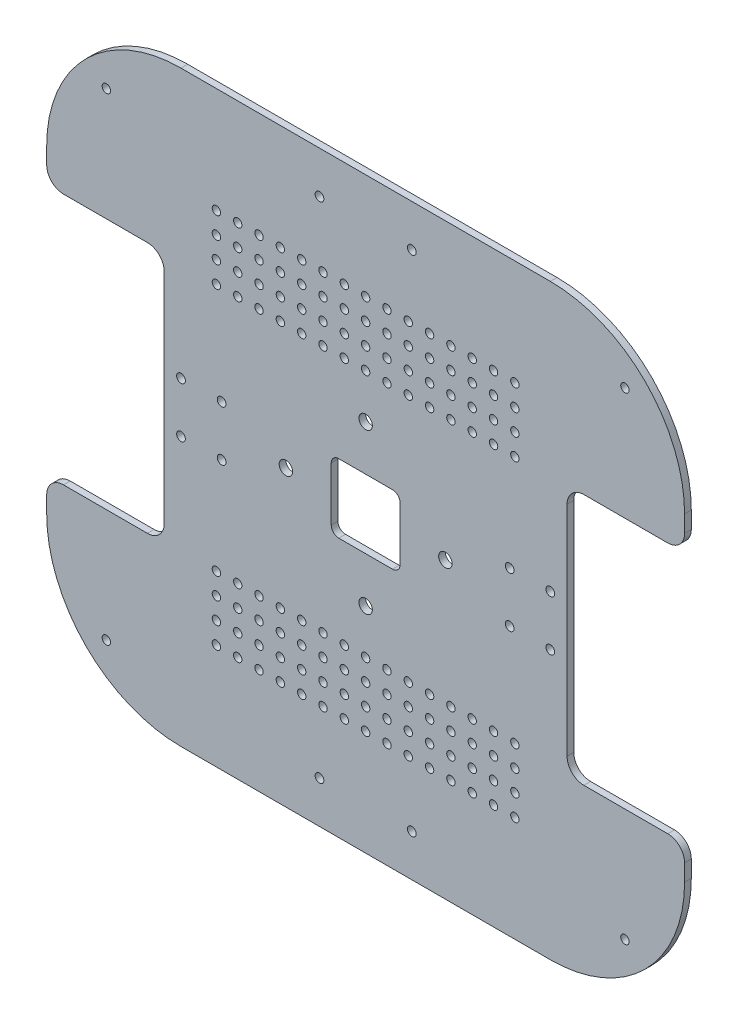
SolidWorks part; units mm, degrees
ref_plane "前视基准面" through (0, 0, 0) normal (0, 0, 1) x (1, 0, 0)
ref_plane "上视基准面" through (0, 0, 0) normal (0, 1, 0) x (1, 0, 0)
ref_plane "右视基准面" through (0, 0, 0) normal (1, 0, 0) x (0, 0, -1)
sketch "草图1" plane through (0, 0, 0) normal (0, 0, 1) x (1, 0, 0)
  line L0 (0, 0) -> (0, 255.003) construction
  line L1 (-190, 175) -> (190, 175)
  line L2 (-190, 175) -> (-190, 75)
  line L3 (-190, -175) -> (190, -175)
  line L4 (190, 175) -> (190, 75)
  line L5 (-190, 175) -> (190, -175) construction
  line L6 (-190, -175) -> (190, 175) construction
  line L7 (-190, -75) -> (-120, -75)
  line L9 (-190, 75) -> (-120, 75)
  line L10 (-120, -75) -> (-120, 75)
  line L11 (0, -175) -> (0, 175) construction
  line L12 (-20.5, -20.5) -> (20.5, -20.5)
  line L13 (190, 75) -> (120, 75)
  line L14 (120, -75) -> (120, 75)
  line L15 (190, -75) -> (120, -75)
  line L17 (190, -75) -> (190, -175)
  line L18 (-190, -75) -> (-190, -175)
  line L19 (-20.5, -20.5) -> (-20.5, 20.5)
  line L20 (-20.5, 20.5) -> (20.5, 20.5)
  line L21 (20.5, -20.5) -> (20.5, 20.5)
  line L22 (-20.5, -20.5) -> (20.5, 20.5) construction
  line L23 (-20.5, 20.5) -> (20.5, -20.5) construction
  line L24 (120, 0) -> (-120, 0) construction
  circle A0 centre (-110, 15) radius 2.6
  circle A1 centre (-85.8, 15) radius 2.6
  circle A2 centre (-85.8, -15) radius 2.6
  circle A3 centre (-110, -15) radius 2.6
  circle A4 centre (85.8, -15) radius 2.6
  circle A5 centre (110, -15) radius 2.6
  circle A6 centre (85.8, 15) radius 2.6
  circle A7 centre (110, 15) radius 2.6
  circle A8 centre (154.4645, 142.2699) radius 2.5
  circle A10 centre (0, 0) radius 210 construction
  circle A11 centre (47.5, 0) radius 4
  circle A12 centre (0, -47.5) radius 4
  circle A13 centre (-154.4645, 142.2699) radius 2.5
  circle A14 centre (-154.4645, -142.2699) radius 2.5
  circle A15 centre (154.4645, -142.2699) radius 2.5
  circle A16 centre (-47.5, 0) radius 4
  circle A17 centre (0, 47.5) radius 4
  circle A18 centre (27.5, -150) radius 2.6
  circle A20 centre (-27.5, -150) radius 2.6
  circle A24 centre (-27.5, 150) radius 2.6
  circle A25 centre (27.5, 150) radius 2.6
  point P0 (0, 0)
  point P56 (0, 0)
  dimension "D5" = 2
  dimension "D7" = 80
  dimension "D11" = 27
  dimension "D13" = 27.5
  dimension "D14" = 25
  dimension "D15" = 15
  dimension "D1" = 380
  dimension "D2" = 350
  dimension "D3" = 150
  dimension "D4" = 100
  dimension "D8" = 24.2
  dimension "D9" = 30
  dimension "D10" = 10
  dimension "D6" = 2
  dimension "D12" = 4
extrude "凸台-拉伸1" add sketch "草图1" along normal blind 4
fillet "圆角1" radius 80 4 edges at (-190, -175, 2) (190, -175, 2) (190, 175, 2) (-190, 175, 2)
fillet "圆角2" radius 10 8 edges at (-120, 75, 2) (-120, -75, 2) (120, 75, 2) (120, -75, 2) (-190, -75, 2) (-190, 75, 2) (190, 75, 2) (190, -75, 2)
fillet "圆角3" radius 4.5 4 edges at (-20.5, 20.5, 2) (20.5, 20.5, 2) (20.5, -20.5, 2) (-20.5, -20.5, 2)
sketch "草图2" plane through (0, 0, 4) normal (0, 0, 1) x (1, 0, 0)
  line L0 (0, 0) -> (236.9862, 0) construction
  circle A0 centre (88.9, 74) radius 2.5
  circle A1 centre (76.2, 74) radius 2.5
  circle A2 centre (63.5, 74) radius 2.5
  circle A3 centre (50.8, 74) radius 2.5
  circle A4 centre (38.1, 74) radius 2.5
  circle A5 centre (25.4, 74) radius 2.5
  circle A6 centre (12.7, 74) radius 2.5
  circle A7 centre (0, 74) radius 2.5
  circle A8 centre (-12.7, 74) radius 2.5
  circle A9 centre (-25.4, 74) radius 2.5
  circle A10 centre (-38.1, 74) radius 2.5
  circle A11 centre (-50.8, 74) radius 2.5
  circle A12 centre (-63.5, 74) radius 2.5
  circle A13 centre (-76.2, 74) radius 2.5
  circle A14 centre (-88.9, 74) radius 2.5
  circle A15 centre (76.2, 86.7) radius 2.5
  circle A16 centre (63.5, 86.7) radius 2.5
  circle A17 centre (50.8, 86.7) radius 2.5
  circle A18 centre (38.1, 86.7) radius 2.5
  circle A19 centre (25.4, 86.7) radius 2.5
  circle A20 centre (12.7, 86.7) radius 2.5
  circle A21 centre (0, 86.7) radius 2.5
  circle A22 centre (-12.7, 86.7) radius 2.5
  circle A23 centre (-25.4, 86.7) radius 2.5
  circle A24 centre (-38.1, 86.7) radius 2.5
  circle A25 centre (-50.8, 86.7) radius 2.5
  circle A26 centre (-63.5, 86.7) radius 2.5
  circle A27 centre (-76.2, 86.7) radius 2.5
  circle A28 centre (-88.9, 86.7) radius 2.5
  circle A29 centre (76.2, 99.4) radius 2.5
  circle A30 centre (63.5, 99.4) radius 2.5
  circle A31 centre (50.8, 99.4) radius 2.5
  circle A32 centre (38.1, 99.4) radius 2.5
  circle A33 centre (25.4, 99.4) radius 2.5
  circle A34 centre (12.7, 99.4) radius 2.5
  circle A35 centre (0, 99.4) radius 2.5
  circle A36 centre (-12.7, 99.4) radius 2.5
  circle A37 centre (-25.4, 99.4) radius 2.5
  circle A38 centre (-38.1, 99.4) radius 2.5
  circle A39 centre (-50.8, 99.4) radius 2.5
  circle A40 centre (-63.5, 99.4) radius 2.5
  circle A41 centre (-76.2, 99.4) radius 2.5
  circle A42 centre (-88.9, 99.4) radius 2.5
  circle A43 centre (76.2, 112.1) radius 2.5
  circle A44 centre (63.5, 112.1) radius 2.5
  circle A45 centre (50.8, 112.1) radius 2.5
  circle A46 centre (38.1, 112.1) radius 2.5
  circle A47 centre (25.4, 112.1) radius 2.5
  circle A48 centre (12.7, 112.1) radius 2.5
  circle A49 centre (0, 112.1) radius 2.5
  circle A50 centre (-12.7, 112.1) radius 2.5
  circle A51 centre (-25.4, 112.1) radius 2.5
  circle A52 centre (-38.1, 112.1) radius 2.5
  circle A53 centre (-50.8, 112.1) radius 2.5
  circle A54 centre (-63.5, 112.1) radius 2.5
  circle A55 centre (-76.2, 112.1) radius 2.5
  circle A56 centre (-88.9, 112.1) radius 2.5
  circle A57 centre (88.9, 86.7) radius 2.5
  circle A58 centre (88.9, 99.4) radius 2.5
  circle A59 centre (88.9, 112.1) radius 2.5
  circle A60 centre (88.9, -112.1) radius 2.5
  circle A61 centre (88.9, -99.4) radius 2.5
  circle A62 centre (88.9, -86.7) radius 2.5
  circle A63 centre (-88.9, -112.1) radius 2.5
  circle A64 centre (-76.2, -112.1) radius 2.5
  circle A65 centre (-63.5, -112.1) radius 2.5
  circle A66 centre (-50.8, -112.1) radius 2.5
  circle A67 centre (-38.1, -112.1) radius 2.5
  circle A68 centre (-25.4, -112.1) radius 2.5
  circle A69 centre (-12.7, -112.1) radius 2.5
  circle A70 centre (0, -112.1) radius 2.5
  circle A71 centre (12.7, -112.1) radius 2.5
  circle A72 centre (25.4, -112.1) radius 2.5
  circle A73 centre (38.1, -112.1) radius 2.5
  circle A74 centre (50.8, -112.1) radius 2.5
  circle A75 centre (63.5, -112.1) radius 2.5
  circle A76 centre (76.2, -112.1) radius 2.5
  circle A77 centre (-88.9, -99.4) radius 2.5
  circle A78 centre (-76.2, -99.4) radius 2.5
  circle A79 centre (-63.5, -99.4) radius 2.5
  circle A80 centre (-50.8, -99.4) radius 2.5
  circle A81 centre (-38.1, -99.4) radius 2.5
  circle A82 centre (-25.4, -99.4) radius 2.5
  circle A83 centre (-12.7, -99.4) radius 2.5
  circle A84 centre (0, -99.4) radius 2.5
  circle A85 centre (12.7, -99.4) radius 2.5
  circle A86 centre (25.4, -99.4) radius 2.5
  circle A87 centre (38.1, -99.4) radius 2.5
  circle A88 centre (50.8, -99.4) radius 2.5
  circle A89 centre (63.5, -99.4) radius 2.5
  circle A90 centre (76.2, -99.4) radius 2.5
  circle A91 centre (-88.9, -86.7) radius 2.5
  circle A92 centre (-76.2, -86.7) radius 2.5
  circle A93 centre (-63.5, -86.7) radius 2.5
  circle A94 centre (-50.8, -86.7) radius 2.5
  circle A95 centre (-38.1, -86.7) radius 2.5
  circle A96 centre (-25.4, -86.7) radius 2.5
  circle A97 centre (-12.7, -86.7) radius 2.5
  circle A98 centre (0, -86.7) radius 2.5
  circle A99 centre (12.7, -86.7) radius 2.5
  circle A100 centre (25.4, -86.7) radius 2.5
  circle A101 centre (38.1, -86.7) radius 2.5
  circle A102 centre (50.8, -86.7) radius 2.5
  circle A103 centre (63.5, -86.7) radius 2.5
  circle A104 centre (76.2, -86.7) radius 2.5
  circle A105 centre (-88.9, -74) radius 2.5
  circle A106 centre (-76.2, -74) radius 2.5
  circle A107 centre (-63.5, -74) radius 2.5
  circle A108 centre (-50.8, -74) radius 2.5
  circle A109 centre (-38.1, -74) radius 2.5
  circle A110 centre (-25.4, -74) radius 2.5
  circle A111 centre (-12.7, -74) radius 2.5
  circle A112 centre (0, -74) radius 2.5
  circle A113 centre (12.7, -74) radius 2.5
  circle A114 centre (25.4, -74) radius 2.5
  circle A115 centre (38.1, -74) radius 2.5
  circle A116 centre (50.8, -74) radius 2.5
  circle A117 centre (63.5, -74) radius 2.5
  circle A118 centre (76.2, -74) radius 2.5
  circle A119 centre (88.9, -74) radius 2.5
extrude "切除-拉伸1" cut sketch "草图2" against normal blind 10
